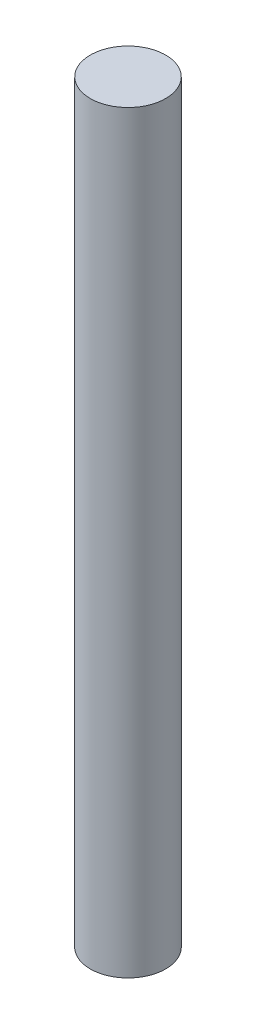
SolidWorks part; units mm, degrees
ref_plane "Front Plane" through (0, 0, 0) normal (0, 0, 1) x (1, 0, 0)
ref_plane "Top Plane" through (0, 0, 0) normal (0, 1, 0) x (1, 0, 0)
ref_plane "Right Plane" through (0, 0, 0) normal (1, 0, 0) x (0, 0, -1)
sketch "Sketch1" plane through (0, 0, 0) normal (0, 1, 0) x (1, 0, 0)
  circle A0 centre (0, 0) radius 50
  dimension "D1" = 100
extrude "Boss-Extrude1" add sketch "Sketch1" along normal blind 1000
ref_point "Point1"
ref_point "Point2"
